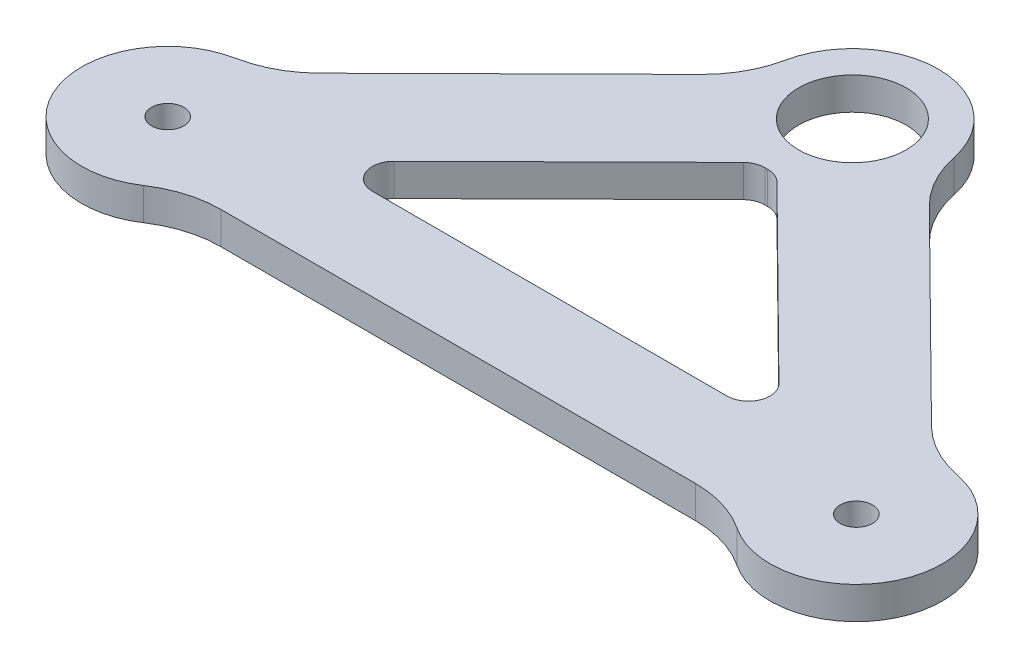
SolidWorks part; units mm, degrees
ref_plane "Front Plane" through (0, 0, 0) normal (0, 0, 1) x (1, 0, 0)
ref_plane "Top Plane" through (0, 0, 0) normal (0, 1, 0) x (1, 0, 0)
ref_plane "Right Plane" through (0, 0, 0) normal (1, 0, 0) x (0, 0, -1)
sketch "Sketch2" plane through (0, 0, 0) normal (0, 1, 0) x (1, 0, 0)
  line L0 (0, 34.3023) -> (0, -20.3488) construction
  line L1 (-35.5154, 1.464) -> (-3.5154, 33.1026)
  line L2 (-28.4846, -5.6471) -> (-0.9255, 21.6008)
  line L3 (-32, -7.0915) -> (32, -7.0915)
  line L4 (32, 2.9085) -> (-32, 2.9085)
  line L5 (35.446, 1.5314) -> (3.5155, 33.1025)
  line L6 (-3.446, 25.9242) -> (0.0006, 22.5164)
  line L7 (0, 22.5158) -> (3.5154, 25.9915)
  line L8 (0.9265, 21.6009) -> (29.3058, -6.459)
  line L9 (-28.4293, 1.4085) -> (28.4293, 1.4085)
  circle A0 centre (-32, -2.0915) radius 5
  circle A1 centre (32, -2.0915) radius 5
  circle A2 centre (0, 29.5471) radius 5
  circle A3 centre (-32, -2.0915) radius 8
  circle A4 centre (0, 29.5471) radius 8
  circle A5 centre (32, -2.0915) radius 8
  circle A6 centre (-32, -2.0915) radius 1.5
  circle A7 centre (32, -2.0915) radius 1.5
  dimension "D3" = 10
  dimension "D4" = 10
  dimension "D5" = 10
  dimension "D6" = 16
  dimension "D7" = 16
  dimension "D8" = 16
  dimension "D9" = 64
  dimension "D11" = 3
  dimension "D12" = 3
  dimension "D1" = 45
  dimension "D2" = 45
  dimension "D10" = 31.6386
  dimension "D13" = 1.5
extrude "Boss-Extrude1" add sketch "Sketch2" along normal blind 3
fillet "Fillet1" radius 10 6 edges at (7.9563, 1.5, -28.7117) (31.0735, 1.5, -5.8546) (25.755, 1.5, 7.0915) (-25.755, 1.5, 7.0915) (-31.0745, 1.5, -5.8548) (-7.9563, 1.5, -28.7119)
fillet "Fillet2" radius 2 4 edges at (0.9265, 1.5, -21.6009) (-0.9255, 1.5, -21.6008) (21.3487, 1.5, -1.4085) (-21.3484, 1.5, -1.4085)
